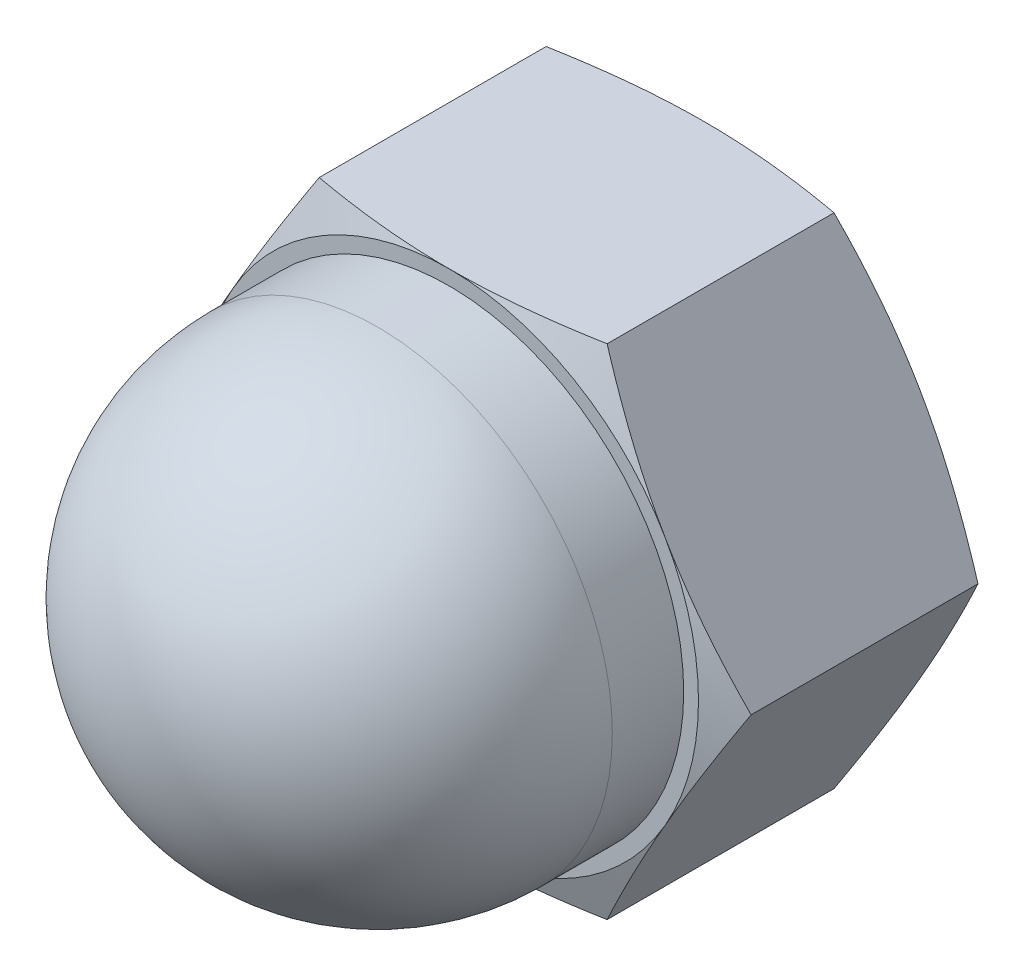
SolidWorks part; units mm, degrees
ref_plane "Front" through (0, 0, 0) normal (0, 0, 1) x (1, 0, 0)
ref_plane "Top" through (0, 0, 0) normal (0, 1, 0) x (1, 0, 0)
ref_plane "Right" through (0, 0, 0) normal (1, 0, 0) x (0, 0, -1)
other "Configuration Table"
sketch "Sketch1" plane through (0, 0, 0) normal (0, 0, 1) x (1, 0, 0)
  line L1 (5.6465, 0) -> (2.8232, 4.89)
  line L2 (2.8232, 4.89) -> (-2.8232, 4.89)
  line L3 (-2.8232, 4.89) -> (-5.6465, 0)
  line L4 (-5.6465, 0) -> (-2.8232, -4.89)
  line L5 (-2.8232, -4.89) -> (2.8232, -4.89)
  line L6 (2.8232, -4.89) -> (5.6465, 0)
  circle A0 centre (0, 0) radius 4.89 construction
  circle A1 centre (0, 0) radius 2.5
extrude "BaseNut" add sketch "Sketch1" against normal blind 5
cosmetic thread "ThreadCosmetic1" [suppressed] parameters "D1"=5, "D2"=6
sketch "Sketch2" plane through (0, 0, 0) normal (0, 1, 0) x (1, 0, 0)
  line L0 (-4.89, 5) -> (-5.6465, 5)
  line L2 (-5.6465, 5) -> (-5.6465, 4.7247)
  line L4 (-5.6465, 4.7247) -> (-4.89, 5)
  line L5 (0, 3.3779) -> (0, -9.1399) construction
  line L7 (-7.1748, 2.5) -> (8.0192, 2.5) construction
  line L8 (-5.6465, 0.2753) -> (-4.89, 0)
  line L9 (-5.6465, 0) -> (-5.6465, 0.2753)
  line L10 (-4.89, 0) -> (-5.6465, 0)
  line L11 (-2.8232, 0) -> (-5.6465, 0) construction
  dimension "D1" = 5.5
  dimension "Angle" = 20
  dimension "h1" = 1.25
revolve "DoubleChamfer" cut sketch "Sketch2" angle 360 about L5
sketch "Sketch3" plane through (-4.6, 0, -6) normal (0, 1, 0) x (-1, 0, 0)
  line L1 (-9.2, 7.4) -> (-9.2, 6)
  line L3 (-4.6, 12) -> (-4.6, 0) construction
  line L4 (0.29, 6) -> (-9.49, 6) construction
  line L5 (-7.85, 6) -> (-9.2, 6)
  line L6 (-7.85, 8) -> (-7.85, 6)
  line L7 (-7.85, 8) -> (-4.6, 11)
  line L8 (-4.6, 12) -> (-4.6, 11)
  line L10 (-4.6, 1) -> (-0.3651, 1) construction
  arc A0 (-4.6, 12) -> (-9.2, 7.4) centre (-4.6, 7.4) ccw
  dimension "h2" = 5
revolve "Crown" add sketch "Sketch3" angle 360 about L3
chamfer "EndChamfer" distance 0.65 angle 30 1 edges at (2.5, 0, -5)
sketch "Sketch4" plane through (0, 0, 0) normal (0, 1, 0) x (1, 0, 0)
  line L0 (0, 7.0607) -> (0, 2.3352) construction
  line L1 (2, 4.6) -> (2.5, 4.6)
  line L2 (2.5, 4.6) -> (2.933, 4.35)
  line L3 (2.933, 4.35) -> (2.5, 4.1)
  line L4 (2.5, 4.1) -> (2, 4.1)
  line L5 (2, 4.1) -> (2, 4.6)
  line L6 (-2.5, 4.35) -> (2.5, 4.35) construction
  dimension "D1" = 0.2705
  dimension "D2" = 2.459
revolve "Cut-Revolve10" [suppressed] cut sketch "Sketch4" angle 360 about L0
pattern_linear "LPattern10" [suppressed] count 8 spacing 0.3246 along (0, 0, 1)
equation "\"h1@Sketch2\" = \"h@BaseNut\" / 2"
equation "\"h2@Sketch3\" = \"m@Sketch3\"-1"
equation "\"D1@Sketch2\" =  \"s@Sketch1\""
equation "\"D2@Sketch4\" = \"d@Sketch1\""
equation "\"D1@Sketch4\" =  ( \"D2@ThreadCosmetic1\" - \"d@Sketch1\" )  / 2"
equation "\"D3@LPattern10\" = \"D1@Sketch4\" * 1.2"
equation "\"D1@LPattern10\" = \"h@BaseNut\" / \"D3@LPattern10\""
